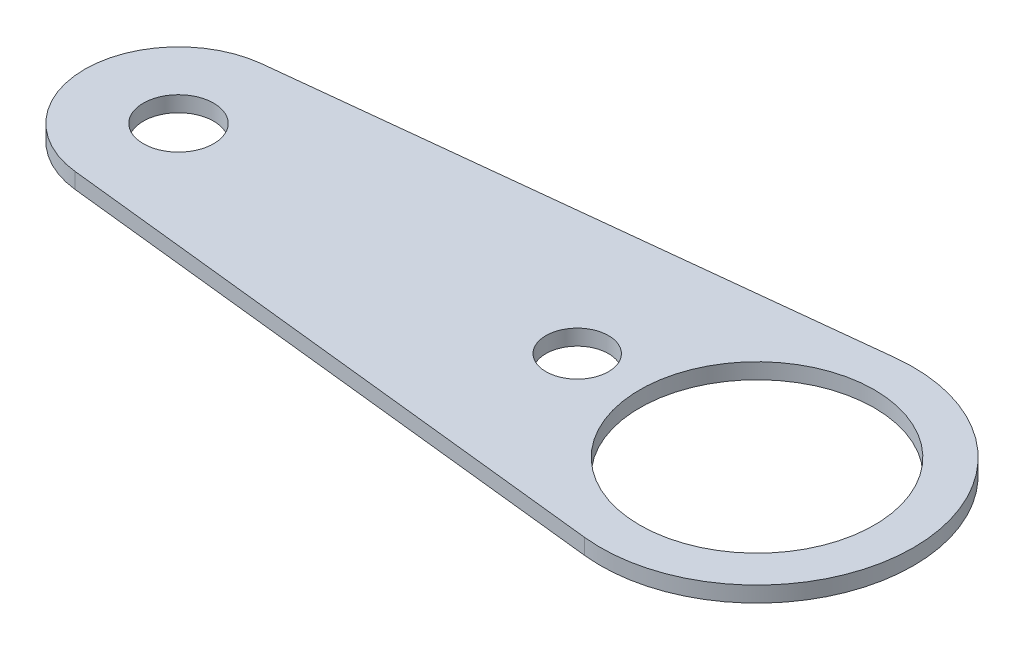
SolidWorks part; units mm, degrees
ref_plane "Front Plane" through (0, 0, 0) normal (0, 0, 1) x (1, 0, 0)
ref_plane "Top Plane" through (0, 0, 0) normal (0, 1, 0) x (1, 0, 0)
ref_plane "Right Plane" through (0, 0, 0) normal (1, 0, 0) x (0, 0, -1)
sketch "Sketch1" plane through (0, 0, 0) normal (0, 1, 0) x (1, 0, 0)
  line L0 (-1.0811, 9.9414) -> (-37.6486, 5.9648)
  line L1 (-1.0811, -9.9414) -> (-37.6486, -5.9648)
  arc A0 (-1.0811, -9.9414) -> (-1.0811, 9.9414) centre (0, 0) ccw
  arc A1 (-37.6486, 5.9648) -> (-37.6486, -5.9648) centre (-37, 0) ccw
  circle A2 centre (-37, 0) radius 2.25
  circle A3 centre (0, 0) radius 7.5
  circle A4 centre (-11.5, 0) radius 2
  dimension "D1" = 20
  dimension "D2" = 12
  dimension "D3" = 37
  dimension "D4" = 15
  dimension "D5" = 4.5
  dimension "D6" = 11.5
  dimension "D7" = 4
extrude "Boss-Extrude1" add sketch "Sketch1" along normal blind 1
